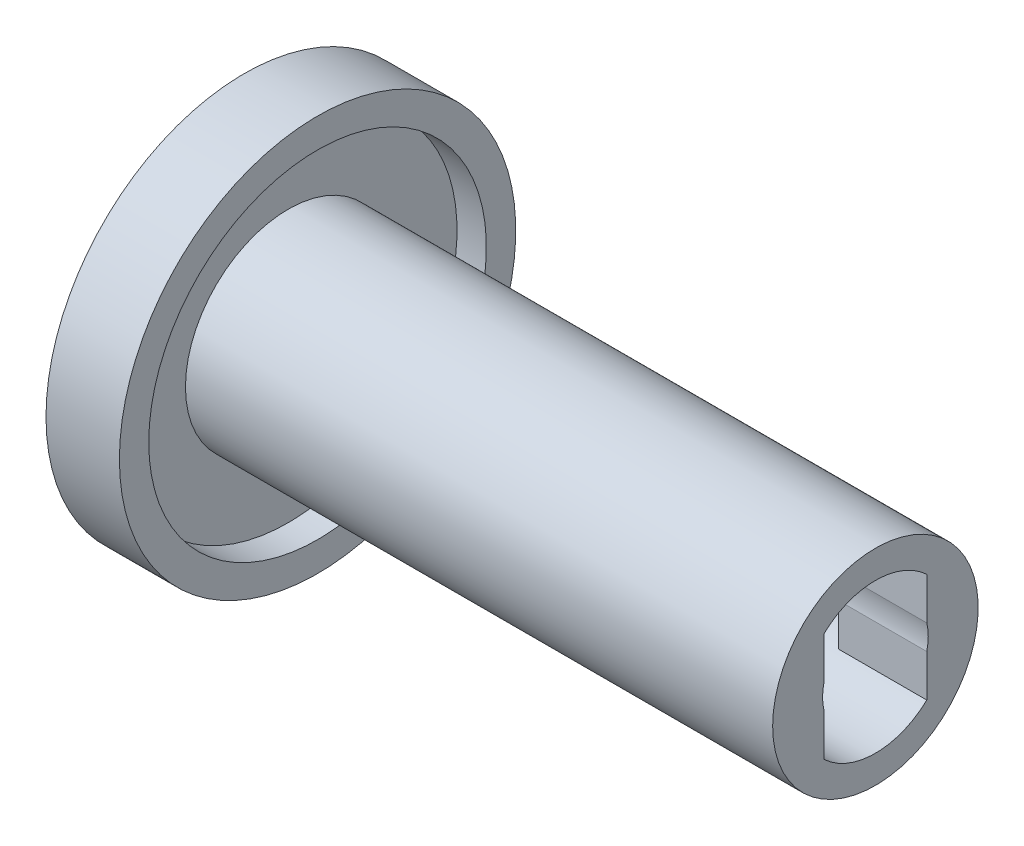
SolidWorks part; units mm, degrees
ref_plane "前视基准面" through (0, 0, 0) normal (0, 0, 1) x (1, 0, 0)
ref_plane "上视基准面" through (0, 0, 0) normal (0, 1, 0) x (1, 0, 0)
ref_plane "右视基准面" through (0, 0, 0) normal (1, 0, 0) x (0, 0, -1)
sketch "草图1" plane through (0, 0, 0) normal (0, 0, 1) x (1, 0, 0)
  line L0 (-81.7412, 0) -> (80.2315, 0) construction
  line L13 (-59.3586, 0) -> (-62.3586, 0)
  line L14 (-62.3586, 0) -> (-62.3586, 13.5)
  line L15 (-62.3586, 13.5) -> (-57.3586, 13.5)
  line L16 (-57.3586, 13.5) -> (-57.3586, 11.5)
  line L17 (-57.3586, 11.5) -> (-59.3586, 11.5)
  line L18 (-59.3586, 11.5) -> (-59.3586, 7)
  line L19 (-59.3586, 7) -> (-19.3586, 7)
  line L20 (-19.3586, 7) -> (-19.3586, 3.6)
  line L21 (-19.3586, 3.6) -> (-25.3586, 3.6)
  line L22 (-25.3586, 3.6) -> (-25.3586, 5.1)
  line L23 (-25.3586, 5.1) -> (-59.3586, 5.1)
  line L24 (-59.3586, 5.1) -> (-59.3586, 0)
  dimension "D1" = 3
  dimension "D2" = 3.4
  dimension "D3" = 1.5
  dimension "D4" = 34
revolve "旋转1" add sketch "草图1" angle 360 about L0
sketch "草图2" plane through (-19.3586, 0, 0) normal (1, 0, 0) x (0, 0, -1)
  line L0 (-15.8872, 0) -> (17.3686, 0) construction
  line L3 (-3.5, 3.7094) -> (-3.5, -3.7094)
  line L5 (3.5, 3.7094) -> (3.5, -3.7094)
  line L6 (-3.5, 10.9922) -> (3.5, -10.9922) construction
  line L7 (-3.5, -10.9922) -> (3.5, 10.9922) construction
  arc A0 (-3.5, 3.7094) -> (3.5, 3.7094) centre (0, 0) cw
  arc A1 (-3.5, -3.7094) -> (3.5, -3.7094) centre (0, 0) ccw
  point P3 (0, 0)
  dimension "D1" = 7
extrude "切除-拉伸1" cut sketch "草图2" against normal blind 6
equation "\"D2@草图1\"=7-3.6"
equation "\"D3@草图1\"=5.1-3.6"
